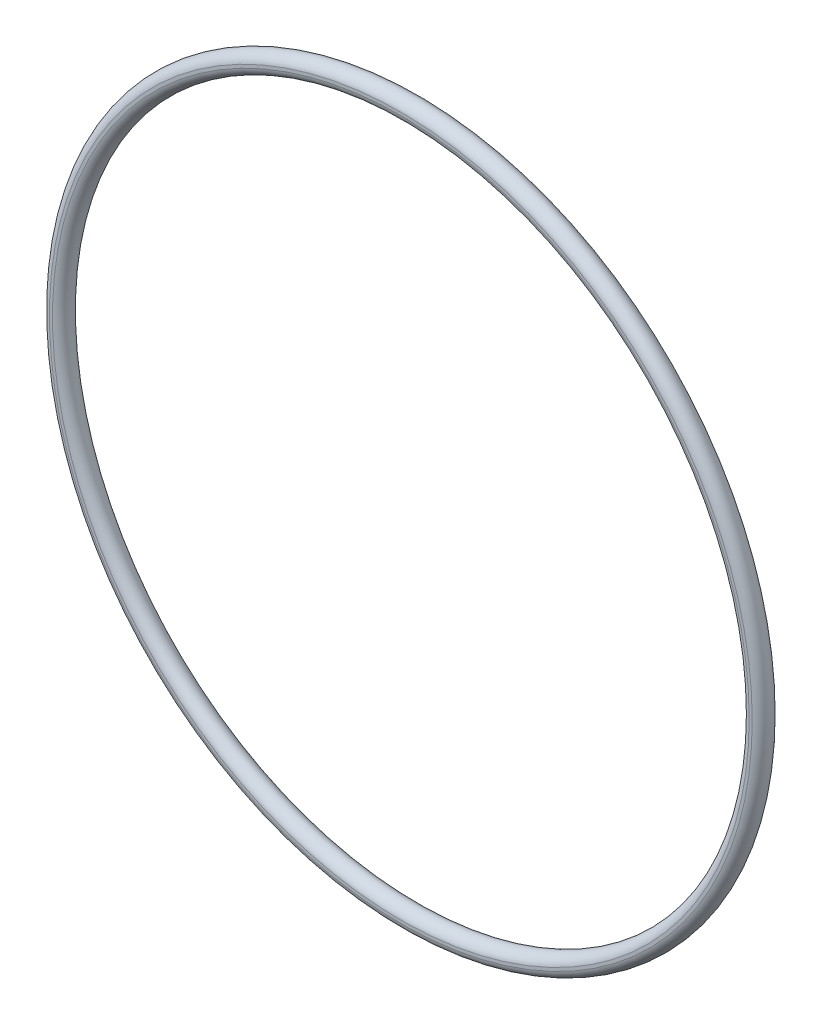
SolidWorks part; units mm, degrees
ref_plane "Front" through (0, 0, 0) normal (0, 0, 1) x (1, 0, 0)
ref_plane "Top" through (0, 0, 0) normal (0, 1, 0) x (1, 0, 0)
ref_plane "Right" through (0, 0, 0) normal (1, 0, 0) x (0, 0, -1)
sketch "Sketch1" plane through (0, 0, 0) normal (1, 0, 0) x (0, -1, 0)
  line L0 (0, -2.667) -> (0, 2.667) construction
  line L2 (-55, 0) -> (55, 0) construction
  line L3 (-89.0397, 0) -> (89.0397, 0) construction
  line L4 (91.3046, -2.6365) -> (92.1088, -2.6365)
  line L5 (91.3046, -2.6365) -> (91.3046, 2.6365)
  line L6 (91.3046, 2.6365) -> (92.1088, 2.6365)
  line L7 (92.1088, -2.6365) -> (92.1088, 2.6365)
  line L8 (91.3046, -2.6365) -> (92.1088, 2.6365) construction
  line L9 (91.3046, 2.6365) -> (92.1088, -2.6365) construction
  circle A0 centre (91.7067, 0) radius 2.667
  point P9 (89.0397, 0)
  point P10 (94.3737, 0)
  point P13 (91.7067, 2.667)
  point P14 (91.7067, -2.667)
  dimension "Width" = 5.334
  dimension "ID" = 178.0794
revolve "Revolve1" add sketch "Sketch1" angle 360 about L0
